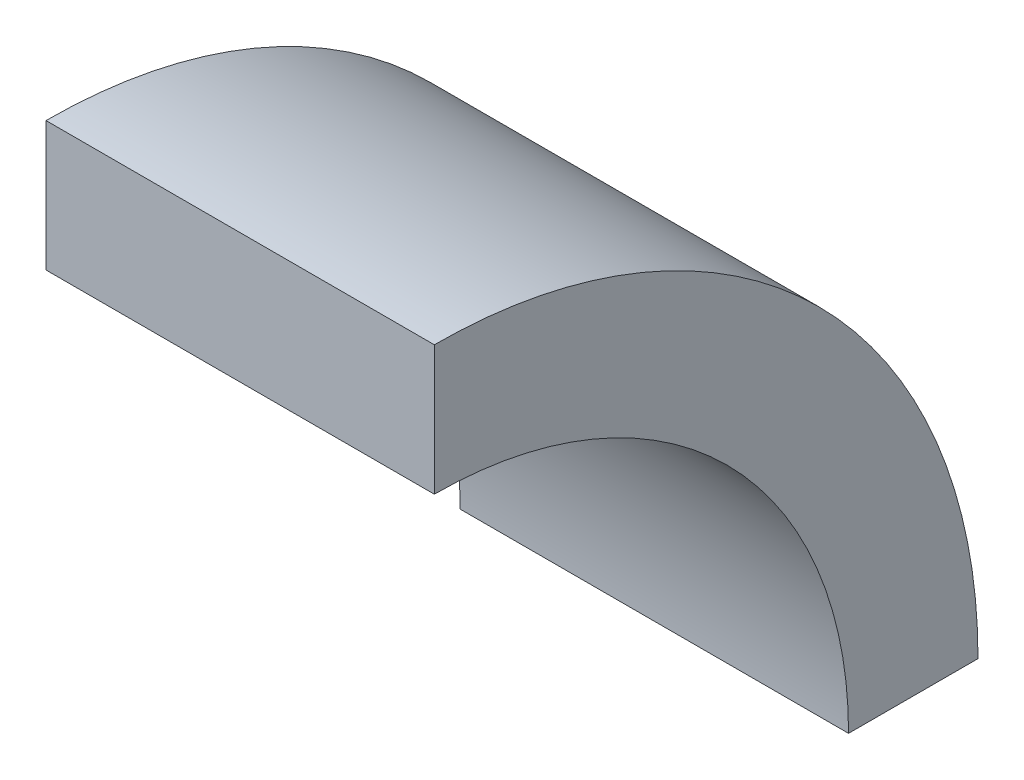
SolidWorks part; units mm, degrees
ref_plane "Front Plane" through (0, 0, 0) normal (0, 0, 1) x (1, 0, 0)
ref_plane "Top Plane" through (0, 0, 0) normal (0, 1, 0) x (1, 0, 0)
ref_plane "Right Plane" through (0, 0, 0) normal (1, 0, 0) x (0, 0, -1)
sketch "Sketch1" plane through (0, 0, 0) normal (0, 1, 0) x (1, 0, 0)
  line L0 (-19.989, -37) -> (20.5317, -37) construction
  line L1 (-15, 5) -> (15, 5)
  line L2 (-15, 5) -> (-15, -5)
  line L3 (-15, -5) -> (15, -5)
  line L4 (15, 5) -> (15, -5)
  line L5 (-15, 5) -> (15, -5) construction
  line L6 (-15, -5) -> (15, 5) construction
  point P0 (0, 0)
  dimension "D1" = 30
  dimension "D2" = 10
  dimension "D3" = 42
revolve "Revolve2" add sketch "Sketch1" angle 90 about L0
